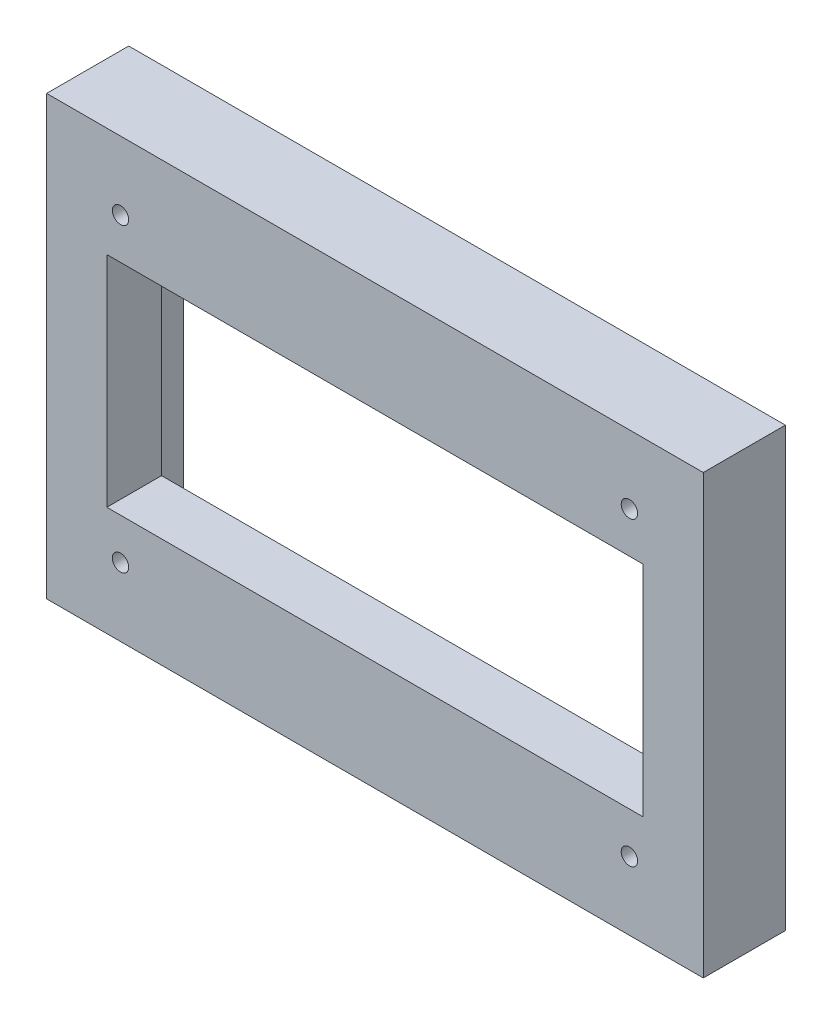
SolidWorks part; units mm, degrees
ref_plane "Front Plane" through (0, 0, 0) normal (0, 0, 1) x (1, 0, 0)
ref_plane "Top Plane" through (0, 0, 0) normal (0, 1, 0) x (1, 0, 0)
ref_plane "Right Plane" through (0, 0, 0) normal (1, 0, 0) x (0, 0, -1)
sketch "Sketch1" plane through (0, 0, 0) normal (0, 0, 1) x (1, 0, 0)
  line L1 (-60, 40) -> (60, 40)
  line L2 (-60, 40) -> (-60, -40)
  line L3 (-60, -40) -> (60, -40)
  line L4 (60, 40) -> (60, -40)
  line L5 (-60, 40) -> (60, -40) construction
  line L6 (-60, -40) -> (60, 40) construction
  point P0 (0, 0)
  dimension "D1" = 120
  dimension "D2" = 80
extrude "Boss-Extrude1" add sketch "Sketch1" against normal blind 10
sketch "Sketch2" plane through (0, 0, -10) normal (0, 0, -1) x (-1, 0, 0)
  line L1 (-49, 20) -> (49, 20)
  line L2 (-49, 20) -> (-49, -20)
  line L3 (-49, -20) -> (49, -20)
  line L4 (49, 20) -> (49, -20)
  line L5 (-49, 20) -> (49, -20) construction
  line L6 (-49, -20) -> (49, 20) construction
  point P0 (0, 0)
  dimension "D1" = 98
  dimension "D2" = 40
extrude "Cut-Extrude2" cut sketch "Sketch2" against normal blind 15 contours L1 L4 L3 L2
sketch "Sketch4" plane through (0, 0, 0) normal (0, 0, 1) x (1, 0, 0)
  circle A0 centre (-46.5, 27.5) radius 1.5
  circle A1 centre (46.5, 27.5) radius 1.5
  circle A2 centre (46.5, -27.5) radius 1.5
  circle A3 centre (-46.5, -27.5) radius 1.5
  dimension "D1" = 3
  dimension "D2" = 27.5
  dimension "D3" = 46.5
  dimension "D6" = 55
  dimension "D4" = 2
  dimension "D5" = 2
extrude "Cut-Extrude3" cut sketch "Sketch4" against normal blind 15
sketch "Sketch5" plane through (0, 0, -10) normal (0, 0, -1) x (-1, 0, 0)
  line L1 (-60, 40) -> (60, 40)
  line L2 (-60, 40) -> (-60, -40)
  line L3 (-60, -40) -> (60, -40)
  line L4 (60, 40) -> (60, -40)
  line L5 (-60, 40) -> (60, -40) construction
  line L6 (-60, -40) -> (60, 40) construction
  point P0 (0, 0)
extrude "Boss-Extrude2" add sketch "Sketch5" along normal blind 5
sketch "Sketch6" plane through (0, 0, -15) normal (0, 0, -1) x (-1, 0, 0)
  line L1 (-50, 30) -> (50, 30)
  line L2 (-50, 30) -> (-50, -30)
  line L3 (-50, -30) -> (50, -30)
  line L4 (50, 30) -> (50, -30)
  line L5 (-50, 30) -> (50, -30) construction
  line L6 (-50, -30) -> (50, 30) construction
  point P0 (0, 0)
  dimension "D1" = 100
  dimension "D2" = 60
extrude "Cut-Extrude5" cut sketch "Sketch6" against normal blind 5
